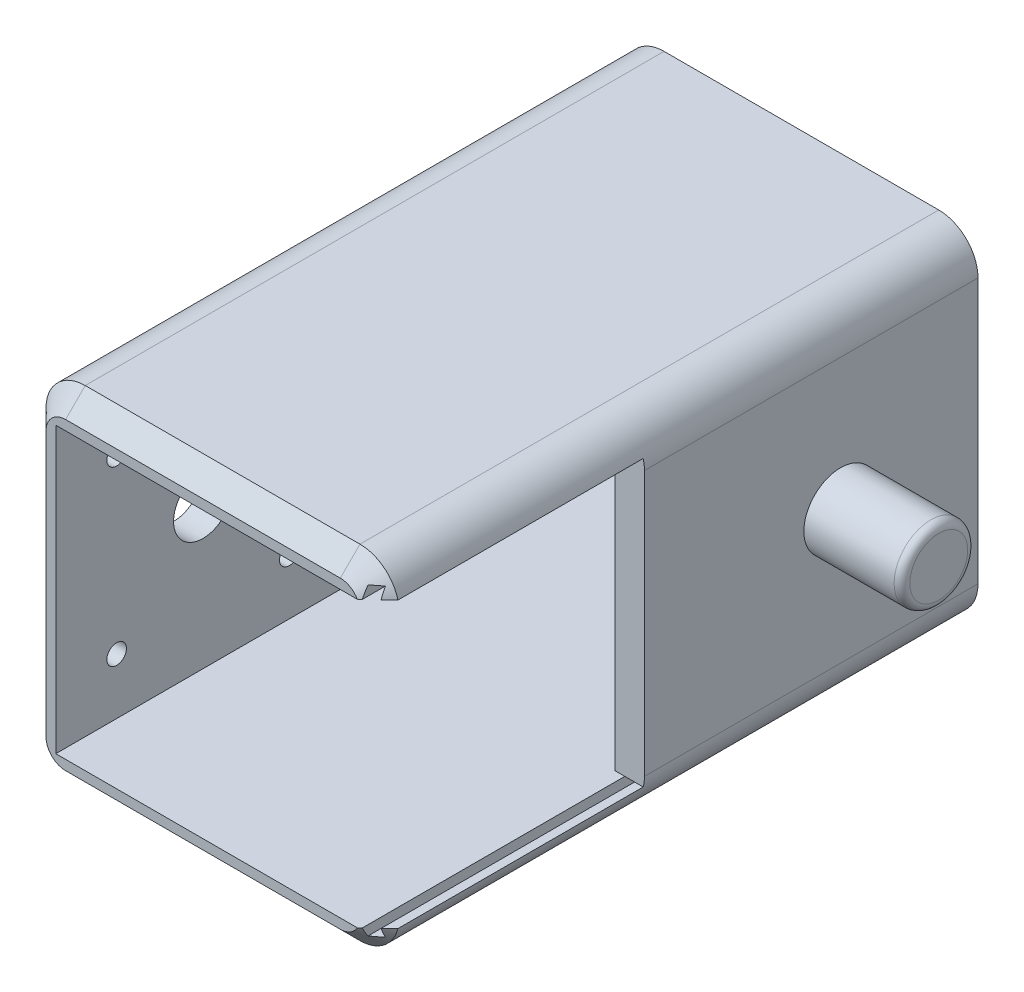
SolidWorks part; units mm, degrees
ref_plane "Front Plane" through (0, 0, 0) normal (0, 0, 1) x (1, 0, 0)
ref_plane "Top Plane" through (0, 0, 0) normal (0, 1, 0) x (1, 0, 0)
ref_plane "Right Plane" through (0, 0, 0) normal (1, 0, 0) x (0, 0, -1)
sketch "Sketch1" plane through (0, 0, 0) normal (0, 0, 1) x (1, 0, 0)
  line L1 (0, 0) -> (-41.91, 0)
  line L2 (0, 0) -> (0, 3.81)
  line L3 (0, 3.81) -> (-45.72, 3.81)
  line L4 (-45.72, 0) -> (-45.72, 3.81)
  line L6 (-45.72, 0) -> (-45.72, -40.64)
  line L7 (-45.72, -40.64) -> (-41.91, -40.64)
  line L8 (-41.91, 0) -> (-41.91, -36.83)
  line L9 (-41.91, -40.64) -> (0, -40.64)
  line L11 (-41.91, -36.83) -> (0, -36.83)
  line L12 (0, -40.64) -> (0, -36.83)
  dimension "D1" = 3.81
  dimension "D2" = 41.91
  dimension "D3" = 36.83
  dimension "D4" = 3.81
extrude "Boss-Extrude1" add sketch "Sketch1" along normal blind 77.47
sketch "Sketch2" plane through (0, 0, 0) normal (1, 0, 0) x (0, 0, -1)
  line L0 (-77.47, -40.64) -> (0, -40.64) construction
  line L1 (0, 3.81) -> (-43.18, 3.81)
  line L2 (0, 3.81) -> (0, -40.64)
  line L3 (0, -40.64) -> (-43.18, -40.64)
  line L4 (-43.18, 3.81) -> (-43.18, -40.64)
  dimension "D1" = 43.18
extrude "Boss-Extrude2" add sketch "Sketch2" against normal blind 3.81
sketch "Sketch3" plane through (-45.72, 0, 0) normal (-1, 0, 0) x (0, 0, 1)
  line L0 (0, -18.415) -> (11.2089, -18.415) construction
  line L2 (0, 3.81) -> (0, -40.64) construction
  line L3 (77.47, 3.81) -> (77.47, -40.64) construction
  line L5 (69.596, -29.591) -> (47.244, -29.591) construction
  line L6 (69.596, -29.591) -> (69.596, -7.239) construction
  line L7 (69.596, -7.239) -> (47.244, -7.239) construction
  line L8 (47.244, -29.591) -> (47.244, -7.239) construction
  line L9 (69.596, -29.591) -> (47.244, -7.239) construction
  line L10 (69.596, -7.239) -> (47.244, -29.591) construction
  circle A0 centre (58.42, -18.415) radius 3.81
  circle A1 centre (47.244, -7.239) radius 1.27
  circle A2 centre (69.596, -7.239) radius 1.27
  circle A3 centre (69.596, -29.591) radius 1.27
  circle A4 centre (47.244, -29.591) radius 1.27
  dimension "D1" = 7.62
  dimension "D4" = 2.54
  dimension "D2" = 19.05
  dimension "D3" = 22.352
extrude "Cut-Extrude1" cut sketch "Sketch3" against normal blind 3.81
sketch "Sketch4" plane through (-45.72, 0, 0) normal (-1, 0, 0) x (0, 0, 1)
  line L0 (0, 3.81) -> (0, -40.64) construction
  circle A0 centre (17.78, -18.415) radius 4.7625
  dimension "D1" = 9.525
  dimension "D2" = 17.78
extrude "Boss-Extrude3" add sketch "Sketch4" along normal blind 12.7
sketch "Sketch5" plane through (0, 0, 0) normal (1, 0, 0) x (0, 0, -1)
  circle A0 centre (-17.78, -18.415) radius 4.7625
  circle A1 centre (-17.78, -18.415) radius 4.7625 construction
extrude "Boss-Extrude4" add sketch "Sketch5" along normal blind 12.7
fillet "Fillet1" radius 1.016 2 edges at (-58.42, -23.1775, 17.78) (12.7, -18.415, 13.0175)
ref_plane "Plane1" through (0, -18.415, 0) normal (0, -1, 0) x (-1, 0, 0)
sketch "Sketch6" plane through (0, 0, 0) normal (0, -1, 0) x (1, 0, 0)
  line L0 (-45.72, 77.47) -> (0, 77.47) construction
  line L1 (-1.27, 39.37) -> (-2.54, 39.37)
  line L2 (-1.27, 39.37) -> (-1.27, 77.47)
  line L3 (-1.27, 77.47) -> (-2.54, 77.47)
  line L4 (-2.54, 39.37) -> (-2.54, 77.47)
  line L5 (-1.27, 39.37) -> (-2.54, 77.47) construction
  line L6 (-1.27, 77.47) -> (-2.54, 39.37) construction
  line L7 (0, 77.47) -> (0, 0) construction
  point P0 (-1.905, 58.42)
  dimension "D1" = 1.27
  dimension "D2" = 1.27
  dimension "D3" = 38.1
extrude "Cut-Extrude2" cut sketch "Sketch6" against normal blind 1.27
mirror "Mirror1" about plane through (0, -18.415, 0) normal (0, -1, 0) of "Cut-Extrude2"
fillet "Fillet2" radius 5.08 4 edges at (-45.72, 3.81, 38.735) (0, 3.81, 38.735) (0, -40.64, 38.735) (-45.72, -40.64, 38.735)
chamfer "Chamfer1" distance 2.54 angle 45 7 edges at (-1.9691, -39.5761, 77.47) (-22.86, -40.64, 77.47) (-44.2321, -39.1521, 77.47) (-45.72, -18.415, 77.47) (-1.9691, 2.7461, 77.47) (-44.2321, 2.3221, 77.47) (-22.86, 3.81, 77.47)
